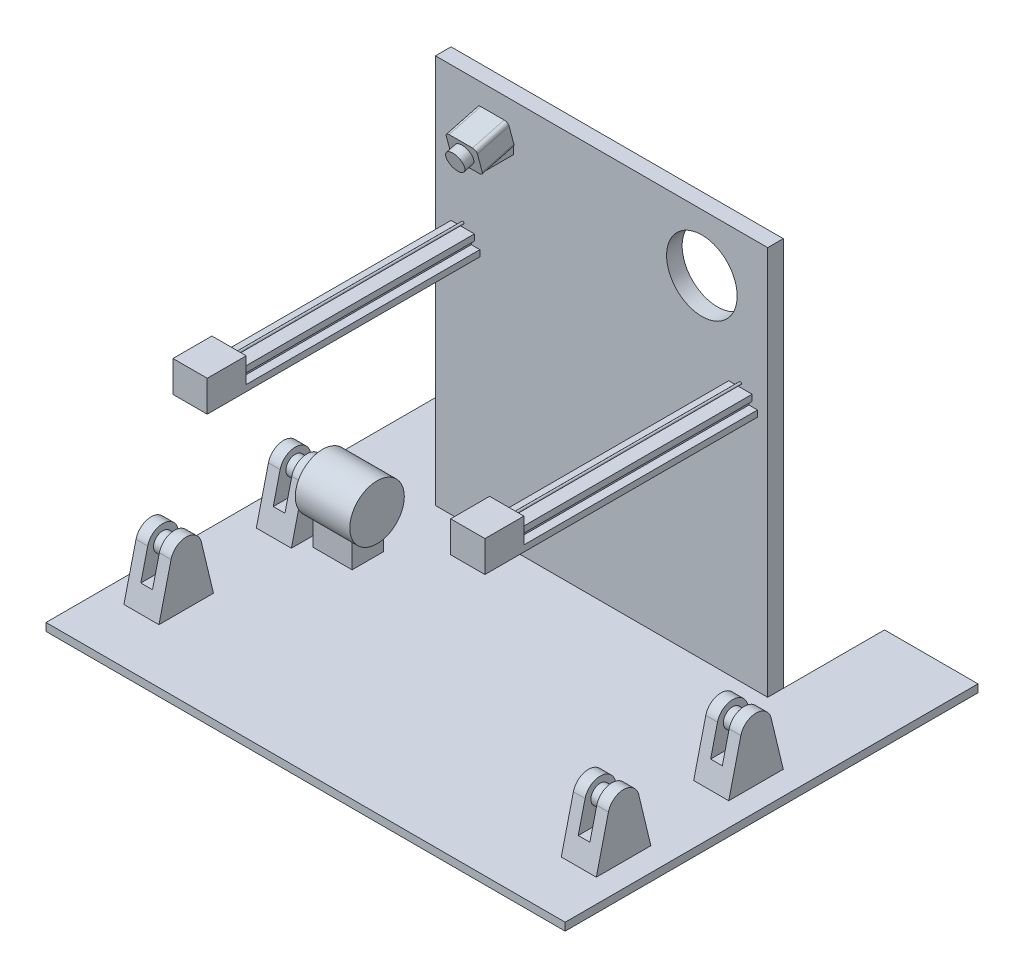
SolidWorks part; units mm, degrees
ref_plane "前视基准面" through (0, 0, 0) normal (0, 0, 1) x (1, 0, 0)
ref_plane "上视基准面" through (0, 0, 0) normal (0, 1, 0) x (1, 0, 0)
ref_plane "右视基准面" through (0, 0, 0) normal (1, 0, 0) x (0, 0, -1)
sketch "草图2" plane through (0, 0, 0) normal (0, 1, 0) x (1, 0, 0)
  line L1 (0, 10) -> (666.5, 10)
  line L2 (0, 10) -> (0, 500)
  line L3 (0, 500) -> (666.5, 500)
  line L4 (666.5, 10) -> (666.5, 500)
extrude "凸台-拉伸1" add sketch "草图2" along normal blind 500
sketch "草图3" plane through (0, 500, 0) normal (0, 1, 0) x (1, 0, 0)
  line L0 (0, 500) -> (0, 10) construction
  line L1 (30, 40) -> (75, 40)
  line L2 (30, 40) -> (30, 110)
  line L3 (30, 110) -> (75, 110)
  line L4 (75, 40) -> (75, 110)
  line L12 (30, 280) -> (75, 280)
  line L13 (75, 210) -> (75, 280)
  line L14 (30, 210) -> (75, 210)
  line L15 (30, 210) -> (30, 280)
  line L24 (636.5, 210) -> (591.5, 210)
  line L25 (636.5, 40) -> (636.5, 110)
  line L26 (591.5, 40) -> (591.5, 110)
  line L27 (636.5, 280) -> (591.5, 280)
  line L28 (636.5, 110) -> (591.5, 110)
  line L29 (636.5, 40) -> (591.5, 40)
  line L30 (591.5, 210) -> (591.5, 280)
  line L31 (636.5, 210) -> (636.5, 280)
  dimension "D1" = 30
extrude "凸台-拉伸2" add sketch "草图3" along normal blind 80
sketch "草图4" plane through (30, 0, 0) normal (-1, 0, 0) x (0, 0, 1)
  line L4 (-245, 580) -> (-245, 500) construction
  line L9 (-280, 580) -> (-210, 580) construction
  line L10 (-280, 500) -> (-210, 500) construction
  line L11 (-75, 580) -> (-75, 500) construction
  line L12 (-110, 580) -> (-40, 580) construction
  line L13 (-110, 500) -> (-40, 500) construction
  line L14 (-280, 500) -> (-264.4456, 564.6766)
  line L15 (-210, 500) -> (-225.5544, 564.6766)
  line L16 (-110, 500) -> (-94.4456, 564.6766)
  line L17 (-40, 500) -> (-55.5544, 564.6766)
  line L18 (-210, 500) -> (-110, 500)
  line L19 (-280, 500) -> (-280, 580)
  line L20 (-280, 580) -> (-280, 590.9085)
  line L21 (-280, 590.9085) -> (-40, 590.9085)
  line L22 (-40, 590.9085) -> (-40, 500)
  arc A6 (-225.5544, 564.6766) -> (-264.4456, 564.6766) centre (-245, 560) ccw
  arc A7 (-55.5544, 564.6766) -> (-94.4456, 564.6766) centre (-75, 560) ccw
extrude "切除-拉伸1" cut sketch "草图4" against normal blind 800
sketch "草图7" plane through (0, 500, 0) normal (0, 1, 0) x (1, 0, 0)
  line L0 (476.5, 370) -> (546.5, 370)
  line L2 (476.5, 370) -> (120, 370)
  line L3 (120, 370) -> (120, 350)
  line L4 (120, 350) -> (476.5, 350)
  line L6 (546.5, 370) -> (546.5, 350)
  line L7 (546.5, 350) -> (476.5, 350)
extrude "凸台-拉伸5" add sketch "草图7" along normal blind 500
sketch "草图8" plane through (0, 0, -350) normal (0, 0, 1) x (1, 0, 0)
  line L0 (177, 805) -> (177, 813)
  line L1 (0, 500) -> (666.5, 500) construction
  line L2 (133, 805) -> (177, 805)
  line L3 (120, 1000) -> (120, 500) construction
  line L6 (133, 813) -> (144, 813)
  line L8 (170, 827) -> (140, 827)
  line L9 (133, 805) -> (133, 813)
  line L10 (140, 827) -> (140, 819)
  line L11 (140, 819) -> (144, 819)
  line L12 (144, 819) -> (144, 813)
  line L13 (166, 819) -> (166, 813)
  line L14 (170, 819) -> (166, 819)
  line L15 (170, 827) -> (170, 819)
  line L16 (166, 813) -> (177, 813)
  line L17 (333.25, 500) -> (333.25, 1000) construction
  line L29 (120, 500) -> (546.5, 500) construction
  line L30 (120, 1000) -> (546.5, 1000) construction
  line L31 (500.5, 813) -> (489.5, 813)
  line L32 (496.5, 827) -> (496.5, 819)
  line L33 (496.5, 819) -> (500.5, 819)
  line L34 (500.5, 819) -> (500.5, 813)
  line L35 (522.5, 819) -> (522.5, 813)
  line L36 (526.5, 819) -> (522.5, 819)
  line L37 (526.5, 827) -> (526.5, 819)
  line L38 (533.5, 805) -> (533.5, 813)
  line L39 (496.5, 827) -> (526.5, 827)
  line L40 (533.5, 813) -> (522.5, 813)
  line L41 (533.5, 805) -> (489.5, 805)
  line L42 (489.5, 805) -> (489.5, 813)
  circle A0 centre (155, 832) radius 1.5
  circle A2 centre (511.5, 832) radius 1.5
  dimension "D1" = 44
  dimension "D13" = 3
  dimension "D2" = 8
  dimension "D3" = 305
  dimension "D4" = 13
  dimension "D5" = 11
  dimension "D6" = 8
  dimension "D7" = 11
  dimension "D8" = 6
  dimension "D9" = 4
  dimension "D10" = 8
  dimension "D11" = 30
  dimension "D12" = 5
  dimension "D14" = 8
extrude "凸台-拉伸6" add sketch "草图8" along normal blind 300
sketch "草图20" plane through (0, 0, 0) normal (0, -1, 0) x (1, 0, 0)
  line L1 (0, 0) -> (751.2789, 0)
  line L2 (0, 0) -> (0, -520)
  line L3 (0, -520) -> (751.2789, -520)
  line L4 (751.2789, 0) -> (751.2789, -520)
extrude "切除-拉伸5" cut sketch "草图20" against normal blind 490
ref_plane "基准面1" through (45, 0, 0) normal (-1, 0, 0) x (0, 0, 1)
sketch "草图22" plane through (45, 0, 0) normal (-1, 0, 0) x (0, 0, 1)
  line L0 (-273.2661, 528) -> (-264.4459, 564.6765)
  line L1 (-225.5544, 564.6766) -> (-216.7339, 528)
  line L2 (-216.7339, 528) -> (-273.2661, 528)
  line L3 (-94.4456, 564.6766) -> (-103.2661, 528)
  line L4 (-103.2661, 528) -> (-46.7339, 528)
  line L5 (-46.7339, 528) -> (-55.5541, 564.6765)
  circle A0 centre (-245, 560) radius 12
  arc A1 (-225.5273, 564.5637) -> (-264.4459, 564.6765) centre (-245, 560) ccw
  circle A2 centre (-75, 560) radius 12
  arc A3 (-55.5541, 564.6765) -> (-94.4727, 564.5637) centre (-75, 560) ccw
extrude "切除-拉伸7" cut sketch "草图22" against normal blind 15
sketch "草图23" plane through (0, 500, 0) normal (0, 1, 0) x (1, 0, 0)
  line L0 (666.5, 500) -> (666.5, 300)
  line L1 (0, 500) -> (120, 500)
  line L2 (0, 500) -> (0, 300)
  line L3 (0, 300) -> (120, 300)
  line L4 (120, 500) -> (120, 300)
  line L5 (546.5, 500) -> (546.5, 300)
  line L6 (546.5, 500) -> (666.5, 500)
  line L7 (546.5, 300) -> (666.5, 300)
extrude "切除-拉伸8" cut sketch "草图23" against normal blind 30
sketch "草图24" plane through (0, 0, -350) normal (0, 0, 1) x (1, 0, 0)
  line L1 (200, 940) -> (220, 940)
  line L2 (200, 940) -> (200, 950)
  line L3 (200, 950) -> (220, 950)
  line L4 (220, 940) -> (220, 950)
extrude "凸台-拉伸10" add sketch "草图24" along normal blind 40
sketch "草图25" plane through (0, 950, 0) normal (0, 1, 0) x (1, 0, 0)
  line L0 (220, 310) -> (220, 350) construction
  line L1 (200, 310) -> (220, 310)
  line L2 (200, 310) -> (200, 325)
  line L3 (200, 325) -> (220, 325)
  line L4 (220, 310) -> (220, 325)
  dimension "D1" = 15
extrude "凸台-拉伸11" add sketch "草图25" along normal blind 10
ref_plane "基准面2" through (0, 141.8078, -529.2339) normal (0, -0.2588, 0.9659) x (1, 0, 0)
sketch "草图26" plane through (0, 141.8078, -529.2339) normal (0, -0.2588, 0.9659) x (1, 0, 0)
  line L1 (190, 839.595) -> (190, 869.595)
  line L2 (190, 869.595) -> (230, 869.595)
  line L3 (230, 869.595) -> (230, 839.595)
  line L9 (230, 839.595) -> (230, 835.595)
  line L10 (230, 835.595) -> (190, 835.595)
  line L11 (190, 835.595) -> (190, 839.595)
extrude "凸台-拉伸12" add sketch "草图26" along normal blind 12 and the other way blind 30
fillet "圆角1" radius 5 4 edges at (190, 951.26, -321.6594) (190, 984.1014, -312.8595) (230, 951.26, -321.6594) (230, 984.1014, -312.8595)
sketch "草图27" plane through (0, 138.702, -517.6428) normal (0, -0.2588, 0.9659) x (1, 0, 0)
  line L0 (210, 869.595) -> (210, 835.595) construction
  line L1 (225, 869.595) -> (195, 869.595) construction
  line L3 (195, 835.595) -> (225, 835.595) construction
  circle A0 centre (210, 852.595) radius 12
extrude "凸台-拉伸13" add sketch "草图27" along normal blind 12
sketch "草图28" plane through (75, 0, 0) normal (1, 0, 0) x (0, 0, -1)
  circle A0 centre (245, 560) radius 12
extrude "凸台-拉伸14" add sketch "草图28" along normal blind 5
sketch "草图29" plane through (80, 0, 0) normal (1, 0, 0) x (0, 0, -1)
  circle A0 centre (245, 560) radius 35
extrude "凸台-拉伸15" add sketch "草图29" along normal blind 70
sketch "草图30" plane through (0, 500, 0) normal (0, 1, 0) x (1, 0, 0)
  line L0 (128, 265) -> (138, 265)
  line L1 (88, 257) -> (88, 265)
  line L2 (88, 265) -> (128, 265)
  line L3 (138, 265) -> (138, 225)
  line L4 (138, 225) -> (128, 225)
  line L5 (88, 225) -> (128, 225)
  line L6 (88, 233) -> (88, 225)
  line L9 (88, 257) -> (88, 233)
extrude "凸台-拉伸16" add sketch "草图30" along normal blind 33
ref_plane "基准面3" through (621.5, 0, 0) normal (1, 0, 0) x (0, 0, -1)
sketch "草图31" plane through (621.5, 0, 0) normal (1, 0, 0) x (0, 0, -1)
  line L0 (46.7339, 528) -> (55.5541, 564.6765)
  line L1 (94.4456, 564.6766) -> (103.2661, 528)
  line L2 (103.2661, 528) -> (46.7339, 528)
  line L3 (225.5544, 564.6766) -> (216.7339, 528)
  line L4 (216.7339, 528) -> (273.2661, 528)
  line L5 (273.2661, 528) -> (264.4459, 564.6765)
  circle A0 centre (75, 560) radius 12
  arc A1 (94.4727, 564.5637) -> (55.5541, 564.6765) centre (75, 560) ccw
  circle A2 centre (245, 560) radius 12
  arc A3 (264.4459, 564.6765) -> (225.5273, 564.5637) centre (245, 560) ccw
extrude "切除-拉伸9" cut sketch "草图31" against normal blind 15
sketch "草图32" plane through (0, 500, 0) normal (0, 1, 0) x (1, 0, 0)
  line L1 (120, 500) -> (546.5, 500)
  line L2 (120, 500) -> (120, 370)
  line L3 (120, 370) -> (546.5, 370)
  line L4 (546.5, 500) -> (546.5, 370)
extrude "切除-拉伸10" cut sketch "草图32" against normal blind 126
sketch "草图34" plane through (546.5, 0, 0) normal (1, 0, 0) x (0, 0, -1)
  line L0 (350, 1000) -> (444.426, 1003.0119) construction
sketch "草图33" plane through (0, 0, -350) normal (0, 0, 1) x (1, 0, 0)
  circle A0 centre (462, 926.5186) radius 45.31
  point P0 (465.0634, 926.5186)
extrude "切除-拉伸11" cut sketch "草图33" along direction (0, 0.0319, -0.9995) on the side against the normal blind 44
sketch "草图35" plane through (0, 0, -50) normal (0, 0, 1) x (1, 0, 0)
  line L1 (133, 805) -> (177, 805)
  line L2 (133, 805) -> (133, 845)
  line L3 (133, 845) -> (177, 845)
  line L4 (177, 805) -> (177, 845)
  line L5 (489.5, 805) -> (533.5, 805)
  line L6 (489.5, 805) -> (489.5, 845)
  line L7 (489.5, 845) -> (533.5, 845)
  line L8 (533.5, 805) -> (533.5, 845)
  dimension "D1" = 40
  dimension "D2" = 40
extrude "凸台-拉伸17" add sketch "草图35" along normal blind 50
sketch "草图37" plane through (0, 0, -10) normal (0, 0, 1) x (1, 0, 0)
  line L1 (0, 490) -> (666.5, 490)
  line L2 (0, 490) -> (0, 500)
  line L3 (0, 500) -> (666.5, 500)
  line L4 (666.5, 490) -> (666.5, 500)
extrude "凸台-拉伸19" add sketch "草图37" along normal blind 40
sketch "草图38" plane through (0, 0, -300) normal (0, 0, -1) x (-1, 0, 0)
  line L0 (-546.5, 1000) -> (-546.5, 490) construction
  line L1 (-666.5, 490) -> (-546.5, 490)
  line L2 (-666.5, 490) -> (-666.5, 500)
  line L3 (-666.5, 500) -> (-546.5, 500)
  line L4 (-546.5, 490) -> (-546.5, 500)
  line L5 (-546.5, 500) -> (-666.5, 500) construction
  line L7 (-120, 490) -> (0, 490)
  line L8 (-120, 490) -> (-120, 500)
  line L9 (-120, 500) -> (0, 500)
  line L10 (0, 490) -> (0, 500)
extrude "凸台-拉伸20" add sketch "草图38" along normal blind 200
sketch "草图40" plane through (0, 0, -350) normal (0, 0, 1) x (1, 0, 0)
  line L1 (120, 1000) -> (546.5, 1000) construction
  line L2 (240, 1000) -> (240, 500)
  line L3 (666.5, 500) -> (0, 500) construction
  line L4 (240, 500) -> (440, 500)
  line L5 (440, 500) -> (440, 850)
  line L6 (440, 850) -> (546.5, 850)
  line L7 (546.5, 1000) -> (546.5, 500) construction
  line L8 (546.5, 850) -> (546.5, 1000)
  line L9 (546.5, 1000) -> (240, 1000)
